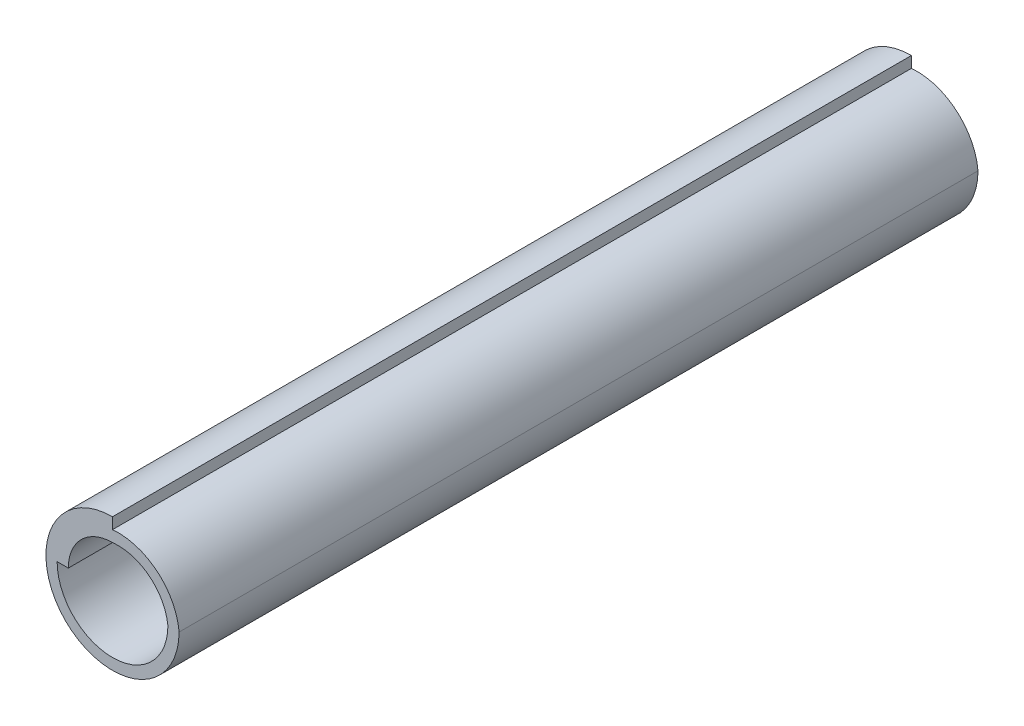
SolidWorks part; units mm, degrees
ref_plane "Plane1" through (0, 0, 0) normal (0, 0, 1) x (1, 0, 0)
ref_plane "Plane2" through (0, 0, 0) normal (0, 1, 0) x (1, 0, 0)
ref_plane "Plane3" through (0, 0, 0) normal (1, 0, 0) x (0, 0, -1)
sketch "Sketch1" plane through (0, 0, 0) normal (0, 0, 1) x (1, 0, 0)
  line L0 (0, 2.08) -> (0, 2.5)
  line L1 (-2.08, 0) -> (-1.66, 0)
  line L2 (0, 1.66) -> (2.08, 0) construction
  line L3 (0.21, -0.21) -> (1.04, 0.83) construction
  line L4 (0, 2.08) -> (2.5, 0) construction
  line L5 (0.21, -0.21) -> (1.25, 1.04) construction
  arc A0 (0, 2.5) -> (2.5, 0) centre (0, 0) ccw
  arc A1 (-2.08, 0) -> (2.08, 0) centre (0, 0) ccw
  arc A2 (0, 1.66) -> (-1.66, 0) centre (0, 0) ccw
  arc A3 (2.08, 0) -> (0, 1.66) centre (0.21, -0.21) ccw
  arc A4 (2.5, 0) -> (0, 2.08) centre (0.21, -0.21) ccw
  dimension "Diameter" = 5
  dimension "D2" = 4.16
  dimension "Thickness" = 0.42
  dimension "D1" = 0.42
extrude "Base-Extrude" add sketch "Sketch1" along normal mid plane 30
equation "\"D1@Sketch1\" = \"Thickness@Sketch1\""
equation "\"D2@Sketch1\" = \"Diameter@Sketch1\" - \"Thickness@Sketch1\" * 2"
